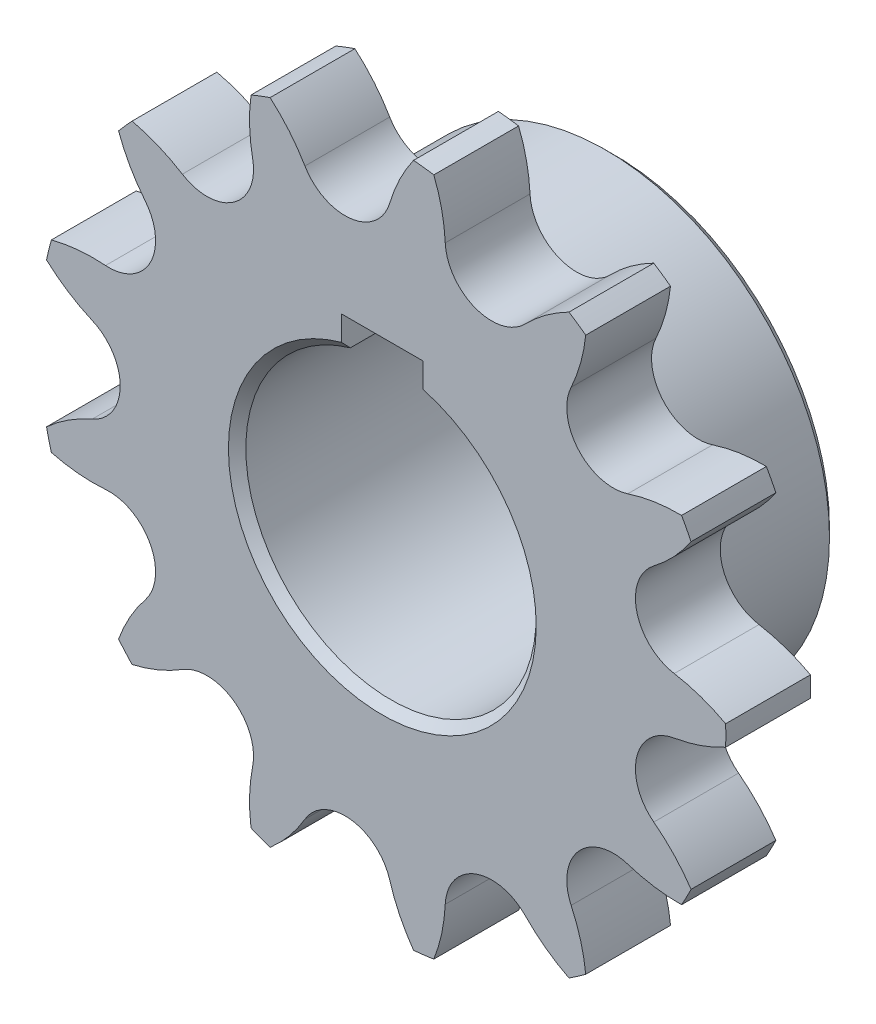
SolidWorks part; units mm, degrees
ref_plane "Front" through (0, 0, 0) normal (0, 0, 1) x (1, 0, 0)
ref_plane "Top" through (0, 0, 0) normal (0, 1, 0) x (1, 0, 0)
ref_plane "Right" through (0, 0, 0) normal (1, 0, 0) x (0, 0, -1)
sketch "Sketch1" plane through (0, 0, 0) normal (0, 0, 1) x (1, 0, 0)
  line L8 (0, -62.1459) -> (0, 62.1459) construction
  line L9 (-62.1459, 0) -> (62.1459, 0) construction
  line L10 (-1.75, -1.75) -> (1.75, 1.75)
  line L11 (-1.75, 1.75) -> (1.75, -1.75)
  circle A292 centre (0, 0) radius 45.128 construction
  circle A293 centre (0, 0) radius 53.068 construction
  arc A294 (46.7425, 19.0976) -> (50.2635, 4.8123) centre (51.603, 12.719) ccw
  arc A295 (59.1199, 1.7544) -> (50.2635, 4.8123) centre (45.489, -23.3702) ccw
  arc A296 (53.1634, 25.9209) -> (51.5328, 29.0278) centre (0, 0) ccw
  arc A297 (46.7425, 19.0976) -> (53.1634, 25.9209) centre (29.4179, 41.8331) ccw
  arc A298 (32.5133, 38.6324) -> (42.2698, 27.6197) centre (39.7814, 35.2432) ccw
  arc A299 (51.5328, 29.0278) -> (42.2698, 27.6197) centre (51.1392, 0.4466) ccw
  arc A300 (35.0278, 47.6581) -> (32.1401, 49.6513) centre (0, 0) ccw
  arc A301 (32.5133, 38.6324) -> (35.0278, 47.6581) centre (6.6074, 50.7125) ccw
  arc A302 (10.8358, 49.317) -> (24.5925, 44.0997) centre (18.8463, 49.6937) ccw
  arc A303 (32.1401, 49.6513) -> (24.5925, 44.0997) centre (45.074, 24.161) ccw
  arc A304 (8.8677, 58.4774) -> (5.3845, 58.9003) centre (0, 0) ccw
  arc A305 (10.8358, 49.317) -> (8.8677, 58.4774) centre (-17.7167, 47.9743) ccw
  arc A306 (-13.3241, 48.7037) -> (1.2814, 50.4771) centre (-6.4062, 52.7599) ccw
  arc A307 (5.3845, 58.9003) -> (1.2814, 50.4771) centre (28.6829, 42.3404) ccw
  arc A308 (-19.3238, 55.9002) -> (-22.6046, 54.6559) centre (0, 0) ccw
  arc A309 (-13.3241, 48.7037) -> (-19.3238, 55.9002) centre (-37.9821, 34.2458) ccw
  arc A310 (-34.4317, 36.9329) -> (-22.3232, 45.2907) centre (-30.1912, 43.7394) ccw
  arc A311 (-22.6046, 54.6559) -> (-22.3232, 45.2907) centre (5.7209, 50.8202) ccw
  arc A312 (-43.0885, 40.5169) -> (-45.4153, 37.8906) centre (0, 0) ccw
  arc A313 (-34.4317, 36.9329) -> (-43.0885, 40.5169) centre (-49.5463, 12.672) ccw
  arc A314 (-47.6513, 16.7013) -> (-40.8139, 29.7288) centre (-47.0597, 24.6988) ccw
  arc A315 (-45.4153, 37.8906) -> (-40.8139, 29.7288) centre (-18.5517, 47.6576) ccw
  arc A316 (-56.9821, 15.8517) -> (-57.8218, 12.4449) centre (0, 0) ccw
  arc A317 (-47.6513, 16.7013) -> (-56.9821, 15.8517) centre (-49.76, -11.8048) ccw
  arc A318 (-49.9546, -7.3564) -> (-49.9546, 7.3564) centre (-53.1474, 0) ccw
  arc A319 (-57.8218, 12.4449) -> (-49.9546, 7.3564) centre (-38.5743, 33.5773) ccw
  arc A320 (-57.8218, -12.4449) -> (-56.9821, -15.8517) centre (0, 0) ccw
  arc A321 (-49.9546, -7.3564) -> (-57.8218, -12.4449) centre (-38.5743, -33.5773) ccw
  arc A322 (-40.8139, -29.7288) -> (-47.6513, -16.7013) centre (-47.0597, -24.6988) ccw
  arc A323 (-56.9821, -15.8517) -> (-47.6513, -16.7013) centre (-49.76, 11.8048) ccw
  arc A324 (-45.4153, -37.8906) -> (-43.0885, -40.5169) centre (0, 0) ccw
  arc A325 (-40.8139, -29.7288) -> (-45.4153, -37.8906) centre (-18.5517, -47.6576) ccw
  arc A326 (-22.3232, -45.2907) -> (-34.4317, -36.9329) centre (-30.1912, -43.7394) ccw
  arc A327 (-43.0885, -40.5169) -> (-34.4317, -36.9329) centre (-49.5463, -12.672) ccw
  arc A328 (-22.6046, -54.6559) -> (-19.3238, -55.9002) centre (0, 0) ccw
  arc A329 (-22.3232, -45.2907) -> (-22.6046, -54.6559) centre (5.7209, -50.8202) ccw
  arc A330 (1.2814, -50.4771) -> (-13.3241, -48.7037) centre (-6.4062, -52.7599) ccw
  arc A331 (-19.3238, -55.9002) -> (-13.3241, -48.7037) centre (-37.9821, -34.2458) ccw
  arc A332 (5.3845, -58.9003) -> (8.8677, -58.4774) centre (0, 0) ccw
  arc A333 (1.2814, -50.4771) -> (5.3845, -58.9003) centre (28.6829, -42.3404) ccw
  arc A334 (24.5925, -44.0997) -> (10.8358, -49.317) centre (18.8463, -49.6937) ccw
  arc A335 (8.8677, -58.4774) -> (10.8358, -49.317) centre (-17.7167, -47.9743) ccw
  arc A336 (32.1401, -49.6513) -> (35.0278, -47.6581) centre (0, 0) ccw
  arc A337 (24.5925, -44.0997) -> (32.1401, -49.6513) centre (45.074, -24.161) ccw
  arc A338 (42.2698, -27.6197) -> (32.5133, -38.6324) centre (39.7814, -35.2432) ccw
  arc A339 (35.0278, -47.6581) -> (32.5133, -38.6324) centre (6.6074, -50.7125) ccw
  arc A340 (51.5328, -29.0278) -> (53.1634, -25.9209) centre (0, 0) ccw
  arc A341 (42.2698, -27.6197) -> (51.5328, -29.0278) centre (51.1392, -0.4466) ccw
  arc A342 (50.2635, -4.8123) -> (46.7425, -19.0976) centre (51.603, -12.719) ccw
  arc A343 (53.1634, -25.9209) -> (46.7425, -19.0976) centre (29.4179, -41.8331) ccw
  arc A344 (59.1199, -1.7544) -> (59.1199, 1.7544) centre (0, 0) ccw
  arc A345 (50.2635, -4.8123) -> (59.1199, -1.7544) centre (45.489, 23.3702) ccw
  circle A346 centre (0, 0) radius 25
  circle A347 centre (0, 0) radius 1.75
sketch "Sketch2" plane through (0, 0, 0) normal (0, 0, 1) x (1, 0, 0)
  circle A226 centre (0, 0) radius 25 construction
  arc A227 (53.1634, 25.9209) -> (51.5328, 29.0278) centre (0, 0) ccw construction
  arc A228 (51.5328, 29.0278) -> (42.2698, 27.6197) centre (51.1392, 0.4466) ccw construction
  arc A229 (32.5133, 38.6324) -> (42.2698, 27.6197) centre (39.7814, 35.2432) ccw construction
  arc A230 (32.5133, 38.6324) -> (35.0278, 47.6581) centre (6.6074, 50.7125) ccw construction
  arc A231 (35.0278, 47.6581) -> (32.1401, 49.6513) centre (0, 0) ccw construction
  arc A232 (32.1401, 49.6513) -> (24.5925, 44.0997) centre (45.074, 24.161) ccw construction
  arc A233 (10.8358, 49.317) -> (24.5925, 44.0997) centre (18.8463, 49.6937) ccw construction
  arc A234 (10.8358, 49.317) -> (8.8677, 58.4774) centre (-17.7167, 47.9743) ccw construction
  arc A235 (8.8677, 58.4774) -> (5.3845, 58.9003) centre (0, 0) ccw construction
  arc A236 (5.3845, 58.9003) -> (1.2814, 50.4771) centre (28.6829, 42.3404) ccw construction
  arc A237 (-13.3241, 48.7037) -> (1.2814, 50.4771) centre (-6.4062, 52.7599) ccw construction
  arc A238 (-13.3241, 48.7037) -> (-19.3238, 55.9002) centre (-37.9821, 34.2458) ccw construction
  arc A239 (-19.3238, 55.9002) -> (-22.6046, 54.6559) centre (0, 0) ccw construction
  arc A240 (-22.6046, 54.6559) -> (-22.3232, 45.2907) centre (5.7209, 50.8202) ccw construction
  arc A241 (-34.4317, 36.9329) -> (-22.3232, 45.2907) centre (-30.1912, 43.7394) ccw construction
  arc A242 (-34.4317, 36.9329) -> (-43.0885, 40.5169) centre (-49.5463, 12.672) ccw construction
  arc A243 (-43.0885, 40.5169) -> (-45.4153, 37.8906) centre (0, 0) ccw construction
  arc A244 (-45.4153, 37.8906) -> (-40.8139, 29.7288) centre (-18.5517, 47.6576) ccw construction
  arc A245 (-47.6513, 16.7013) -> (-40.8139, 29.7288) centre (-47.0597, 24.6988) ccw construction
  arc A246 (-47.6513, 16.7013) -> (-56.9821, 15.8517) centre (-49.76, -11.8048) ccw construction
  arc A247 (-56.9821, 15.8517) -> (-57.8218, 12.4449) centre (0, 0) ccw construction
  arc A248 (-57.8218, 12.4449) -> (-49.9546, 7.3564) centre (-38.5743, 33.5773) ccw construction
  arc A249 (-49.9546, -7.3564) -> (-49.9546, 7.3564) centre (-53.1474, 0) ccw construction
  arc A250 (-49.9546, -7.3564) -> (-57.8218, -12.4449) centre (-38.5743, -33.5773) ccw construction
  arc A251 (-57.8218, -12.4449) -> (-56.9821, -15.8517) centre (0, 0) ccw construction
  arc A252 (-56.9821, -15.8517) -> (-47.6513, -16.7013) centre (-49.76, 11.8048) ccw construction
  arc A253 (-40.8139, -29.7288) -> (-47.6513, -16.7013) centre (-47.0597, -24.6988) ccw construction
  arc A254 (-40.8139, -29.7288) -> (-45.4153, -37.8906) centre (-18.5517, -47.6576) ccw construction
  arc A255 (-45.4153, -37.8906) -> (-43.0885, -40.5169) centre (0, 0) ccw construction
  arc A256 (-43.0885, -40.5169) -> (-34.4317, -36.9329) centre (-49.5463, -12.672) ccw construction
  arc A257 (-22.3232, -45.2907) -> (-34.4317, -36.9329) centre (-30.1912, -43.7394) ccw construction
  arc A258 (-22.3232, -45.2907) -> (-22.6046, -54.6559) centre (5.7209, -50.8202) ccw construction
  arc A259 (-22.6046, -54.6559) -> (-19.3238, -55.9002) centre (0, 0) ccw construction
  arc A260 (-19.3238, -55.9002) -> (-13.3241, -48.7037) centre (-37.9821, -34.2458) ccw construction
  arc A261 (1.2814, -50.4771) -> (-13.3241, -48.7037) centre (-6.4062, -52.7599) ccw construction
  arc A262 (1.2814, -50.4771) -> (5.3845, -58.9003) centre (28.6829, -42.3404) ccw construction
  arc A263 (5.3845, -58.9003) -> (8.8677, -58.4774) centre (0, 0) ccw construction
  arc A264 (8.8677, -58.4774) -> (10.8358, -49.317) centre (-17.7167, -47.9743) ccw construction
  arc A265 (24.5925, -44.0997) -> (10.8358, -49.317) centre (18.8463, -49.6937) ccw construction
  arc A266 (24.5925, -44.0997) -> (32.1401, -49.6513) centre (45.074, -24.161) ccw construction
  arc A267 (32.1401, -49.6513) -> (35.0278, -47.6581) centre (0, 0) ccw construction
  arc A268 (35.0278, -47.6581) -> (32.5133, -38.6324) centre (6.6074, -50.7125) ccw construction
  arc A269 (42.2698, -27.6197) -> (32.5133, -38.6324) centre (39.7814, -35.2432) ccw construction
  arc A270 (42.2698, -27.6197) -> (51.5328, -29.0278) centre (51.1392, -0.4466) ccw construction
  arc A271 (51.5328, -29.0278) -> (53.1634, -25.9209) centre (0, 0) ccw construction
  arc A272 (53.1634, -25.9209) -> (46.7425, -19.0976) centre (29.4179, -41.8331) ccw construction
  arc A273 (50.2635, -4.8123) -> (46.7425, -19.0976) centre (51.603, -12.719) ccw construction
  arc A274 (50.2635, -4.8123) -> (59.1199, -1.7544) centre (45.489, 23.3702) ccw construction
  arc A275 (59.1199, -1.7544) -> (59.1199, 1.7544) centre (0, 0) ccw construction
  arc A276 (59.1199, 1.7544) -> (50.2635, 4.8123) centre (45.489, -23.3702) ccw construction
  arc A277 (46.7425, 19.0976) -> (50.2635, 4.8123) centre (51.603, 12.719) ccw construction
  arc A278 (46.7425, 19.0976) -> (53.1634, 25.9209) centre (29.4179, 41.8331) ccw construction
  circle A279 centre (0, 0) radius 25
  arc A280 (53.1634, 25.9209) -> (51.5328, 29.0278) centre (0, 0) ccw
  arc A281 (51.5328, 29.0278) -> (42.2698, 27.6197) centre (51.1392, 0.4466) ccw
  arc A282 (32.5133, 38.6324) -> (42.2698, 27.6197) centre (39.7814, 35.2432) ccw
  arc A283 (32.5133, 38.6324) -> (35.0278, 47.6581) centre (6.6074, 50.7125) ccw
  arc A284 (35.0278, 47.6581) -> (32.1401, 49.6513) centre (0, 0) ccw
  arc A285 (32.1401, 49.6513) -> (24.5925, 44.0997) centre (45.074, 24.161) ccw
  arc A286 (10.8358, 49.317) -> (24.5925, 44.0997) centre (18.8463, 49.6937) ccw
  arc A287 (10.8358, 49.317) -> (8.8677, 58.4774) centre (-17.7167, 47.9743) ccw
  arc A288 (8.8677, 58.4774) -> (5.3845, 58.9003) centre (0, 0) ccw
  arc A289 (5.3845, 58.9003) -> (1.2814, 50.4771) centre (28.6829, 42.3404) ccw
  arc A290 (-13.3241, 48.7037) -> (1.2814, 50.4771) centre (-6.4062, 52.7599) ccw
  arc A291 (-13.3241, 48.7037) -> (-19.3238, 55.9002) centre (-37.9821, 34.2458) ccw
  arc A292 (-19.3238, 55.9002) -> (-22.6046, 54.6559) centre (0, 0) ccw
  arc A293 (-22.6046, 54.6559) -> (-22.3232, 45.2907) centre (5.7209, 50.8202) ccw
  arc A294 (-34.4317, 36.9329) -> (-22.3232, 45.2907) centre (-30.1912, 43.7394) ccw
  arc A295 (-34.4317, 36.9329) -> (-43.0885, 40.5169) centre (-49.5463, 12.672) ccw
  arc A296 (-43.0885, 40.5169) -> (-45.4153, 37.8906) centre (0, 0) ccw
  arc A297 (-45.4153, 37.8906) -> (-40.8139, 29.7288) centre (-18.5517, 47.6576) ccw
  arc A298 (-47.6513, 16.7013) -> (-40.8139, 29.7288) centre (-47.0597, 24.6988) ccw
  arc A299 (-47.6513, 16.7013) -> (-56.9821, 15.8517) centre (-49.76, -11.8048) ccw
  arc A300 (-56.9821, 15.8517) -> (-57.8218, 12.4449) centre (0, 0) ccw
  arc A301 (-57.8218, 12.4449) -> (-49.9546, 7.3564) centre (-38.5743, 33.5773) ccw
  arc A302 (-49.9546, -7.3564) -> (-49.9546, 7.3564) centre (-53.1474, 0) ccw
  arc A303 (-49.9546, -7.3564) -> (-57.8218, -12.4449) centre (-38.5743, -33.5773) ccw
  arc A304 (-57.8218, -12.4449) -> (-56.9821, -15.8517) centre (0, 0) ccw
  arc A305 (-56.9821, -15.8517) -> (-47.6513, -16.7013) centre (-49.76, 11.8048) ccw
  arc A306 (-40.8139, -29.7288) -> (-47.6513, -16.7013) centre (-47.0597, -24.6988) ccw
  arc A307 (-40.8139, -29.7288) -> (-45.4153, -37.8906) centre (-18.5517, -47.6576) ccw
  arc A308 (-45.4153, -37.8906) -> (-43.0885, -40.5169) centre (0, 0) ccw
  arc A309 (-43.0885, -40.5169) -> (-34.4317, -36.9329) centre (-49.5463, -12.672) ccw
  arc A310 (-22.3232, -45.2907) -> (-34.4317, -36.9329) centre (-30.1912, -43.7394) ccw
  arc A311 (-22.3232, -45.2907) -> (-22.6046, -54.6559) centre (5.7209, -50.8202) ccw
  arc A312 (-22.6046, -54.6559) -> (-19.3238, -55.9002) centre (0, 0) ccw
  arc A313 (-19.3238, -55.9002) -> (-13.3241, -48.7037) centre (-37.9821, -34.2458) ccw
  arc A314 (1.2814, -50.4771) -> (-13.3241, -48.7037) centre (-6.4062, -52.7599) ccw
  arc A315 (1.2814, -50.4771) -> (5.3845, -58.9003) centre (28.6829, -42.3404) ccw
  arc A316 (5.3845, -58.9003) -> (8.8677, -58.4774) centre (0, 0) ccw
  arc A317 (8.8677, -58.4774) -> (10.8358, -49.317) centre (-17.7167, -47.9743) ccw
  arc A318 (24.5925, -44.0997) -> (10.8358, -49.317) centre (18.8463, -49.6937) ccw
  arc A319 (24.5925, -44.0997) -> (32.1401, -49.6513) centre (45.074, -24.161) ccw
  arc A320 (32.1401, -49.6513) -> (35.0278, -47.6581) centre (0, 0) ccw
  arc A321 (35.0278, -47.6581) -> (32.5133, -38.6324) centre (6.6074, -50.7125) ccw
  arc A322 (42.2698, -27.6197) -> (32.5133, -38.6324) centre (39.7814, -35.2432) ccw
  arc A323 (42.2698, -27.6197) -> (51.5328, -29.0278) centre (51.1392, -0.4466) ccw
  arc A324 (51.5328, -29.0278) -> (53.1634, -25.9209) centre (0, 0) ccw
  arc A325 (53.1634, -25.9209) -> (46.7425, -19.0976) centre (29.4179, -41.8331) ccw
  arc A326 (50.2635, -4.8123) -> (46.7425, -19.0976) centre (51.603, -12.719) ccw
  arc A453 (50.2635, -4.8123) -> (59.1199, -1.7544) centre (45.489, 23.3702) ccw
  arc A454 (59.1199, -1.7544) -> (59.1199, 1.7544) centre (0, 0) ccw
  arc A455 (59.1199, 1.7544) -> (50.2635, 4.8123) centre (45.489, -23.3702) ccw
  arc A456 (46.7425, 19.0976) -> (50.2635, 4.8123) centre (51.603, 12.719) ccw
  arc A457 (46.7425, 19.0976) -> (53.1634, 25.9209) centre (29.4179, 41.8331) ccw
extrude "Boss-Extrude1" add sketch "Sketch2" along normal blind 14.6
sketch "Sketch3" plane through (0, 0, 14.6) normal (0, 0, 1) x (1, 0, 0)
  circle A0 centre (0, 0) radius 25
  circle A1 centre (0, 0) radius 38.5
  dimension "D1" = 77
  dimension "D2" = 50
extrude "Boss-Extrude2" add sketch "Sketch3" against normal blind 40
sketch "Sketch4" plane through (0, 0, 14.6) normal (0, 0, 1) x (1, 0, 0)
  line L9 (-7, 20.5) -> (7, 20.5)
  line L10 (-7, 20.5) -> (-7, 29.5)
  line L11 (-7, 29.5) -> (7, 29.5)
  line L12 (7, 20.5) -> (7, 29.5)
  line L13 (-7, 20.5) -> (7, 29.5) construction
  line L14 (-7, 29.5) -> (7, 20.5) construction
  circle A0 centre (0, 0) radius 25 construction
  point P0 (0, 25)
  dimension "D1" = 14
  dimension "D2" = 9
extrude "Cut-Extrude1" cut sketch "Sketch4" against normal blind 45
other "Move Face1" face at (0, 29.5, -5.4) parameters "D1"=0.3
chamfer "Chamfer3" distance 1.5 angle 45 3 edges at (38.5, 0, -25.4) (0, -25, -25.4) (0, -25, 14.6)
chamfer "Chamfer4" distance 3 angle 45 1 edges at (38.5, 0, 0)
